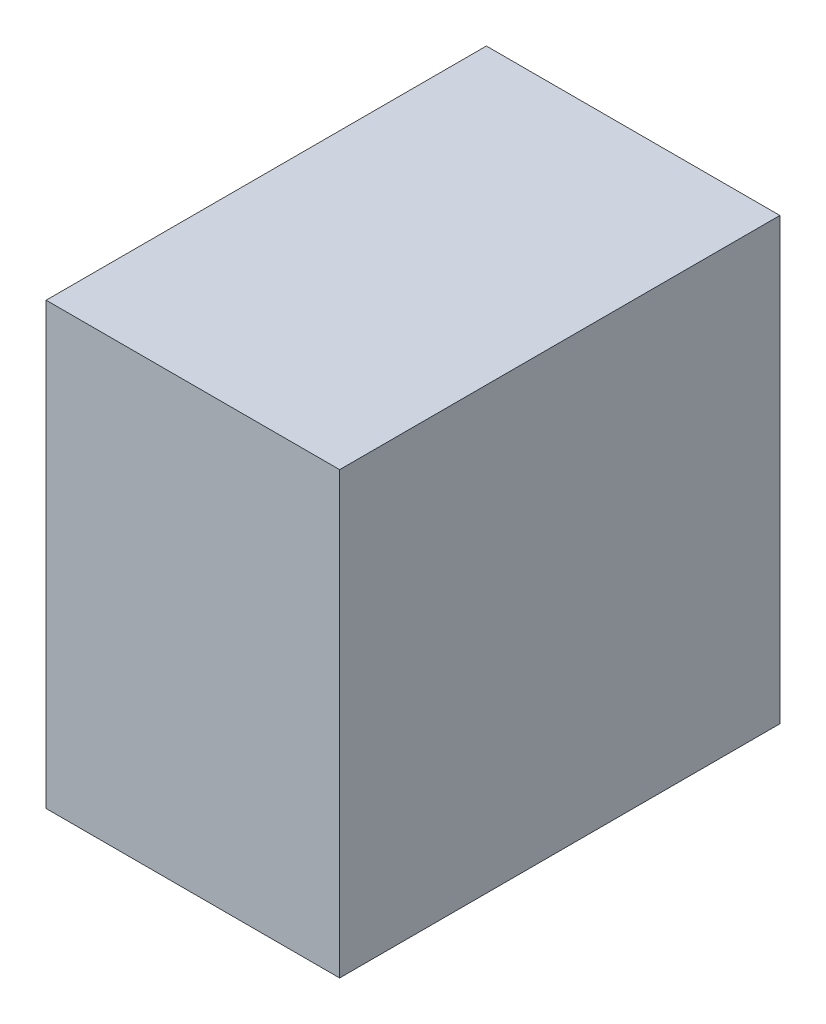
SolidWorks part; units mm, degrees
material "Pine"
ref_plane "Front Plane" through (0, 0, 0) normal (0, 0, 1) x (1, 0, 0)
ref_plane "Top Plane" through (0, 0, 0) normal (0, 1, 0) x (1, 0, 0)
ref_plane "Right Plane" through (0, 0, 0) normal (1, 0, 0) x (0, 0, -1)
sketch "Sketch1" plane through (0, 0, 0) normal (1, 0, 0) x (0, 0, -1)
  line L0 (0, 44.2539) -> (0, -44.2539) construction
  line L1 (-15, 15) -> (15, 15)
  line L2 (-15, 15) -> (-15, -15)
  line L3 (-15, -15) -> (15, -15)
  line L4 (15, 15) -> (15, -15)
  line L5 (55, 0) -> (-55, 0) construction
  point P4 (0, 15)
  point P7 (-15, 0)
  dimension "D1" = 30
  dimension "D2" = 30
extrude "Boss-Extrude1" add sketch "Sketch1" along normal mid plane 20
